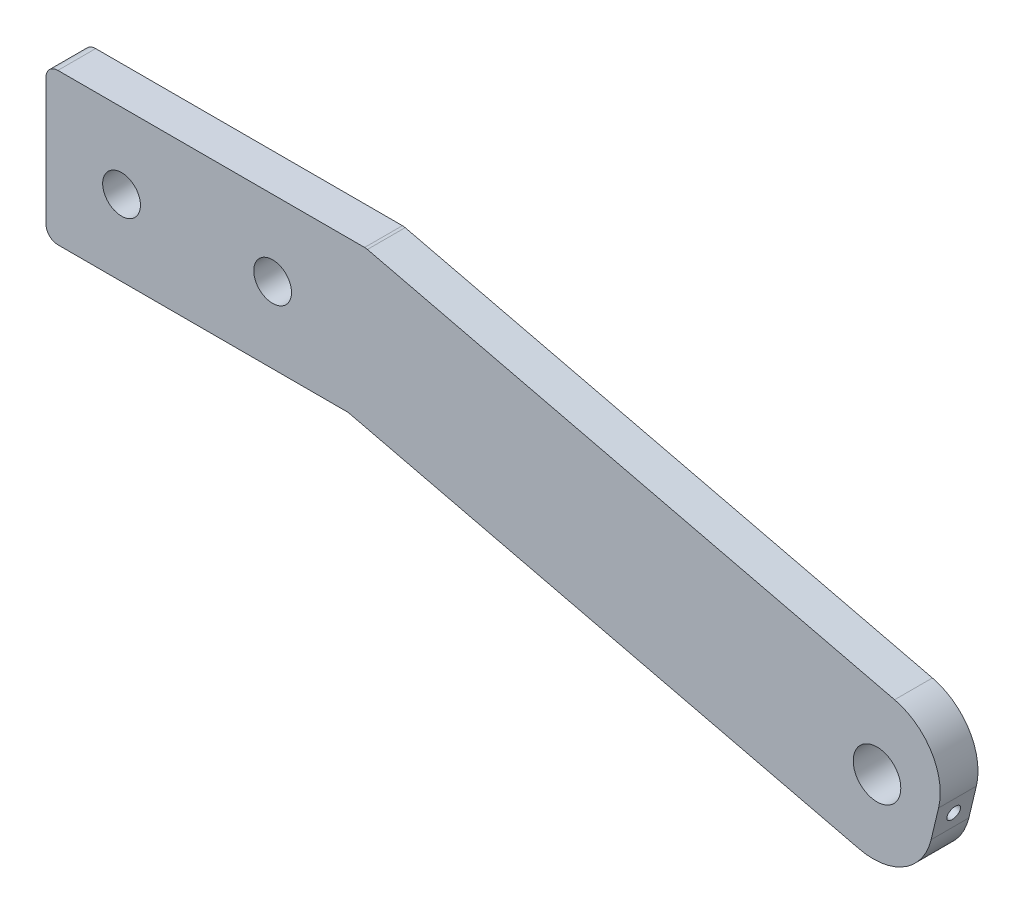
SolidWorks part; units mm, degrees
ref_plane "Front Plane" through (0, 0, 0) normal (0, 0, 1) x (1, 0, 0)
ref_plane "Top Plane" through (0, 0, 0) normal (0, 1, 0) x (1, 0, 0)
ref_plane "Right Plane" through (0, 0, 0) normal (1, 0, 0) x (0, 0, -1)
sketch "Sketch1" plane through (0, 0, 0) normal (0, 0, 1) x (1, 0, 0)
  line L0 (-25.4, 0) -> (-38.1, 0) construction
  line L2 (-38.1, -12.7) -> (-38.1, 12.7)
  line L5 (104.5604, -8.5999) -> (98.6396, -33.3001) construction
  line L6 (12.7, -12.7) -> (71.3084, -26.7487) construction
  line L19 (-25.4, 0) -> (0, 0) construction
  line L25 (15.7017, 12.7) -> (-38.1, 12.7)
  line L26 (12.7, -12.7) -> (-38.1, -12.7)
  line L27 (15.7017, 12.7) -> (74.6646, -1.4337) construction
  line L28 (15.7017, 12.7) -> (114.2849, -10.9309)
  line L29 (12.7, -12.7) -> (108.3641, -35.6312)
  line L30 (108.3641, -35.6312) -> (114.2849, -10.9309)
  circle A0 centre (-25.4, 0) radius 3.175
  circle A12 centre (0, 0) radius 3.175
  circle A13 centre (101.6, -20.95) radius 4
  point P8 (0, 0)
  point P16 (64.2348, -43.9487)
  point P17 (0, 0)
  dimension "D4" = 6.35
  dimension "D7" = 10
  dimension "D8" = 25.4
  dimension "D5" = 101.6
  dimension "D6" = 20.95
  dimension "D9" = 8
  dimension "D2" = 50.8
  dimension "D3" = 12.7
  dimension "D12" = 25.4
  dimension "D13" = 25.4
extrude "Boss-Extrude1" add sketch "Sketch1" along normal blind 6.35
sketch "Sketch3" plane through (110.5529, -26.5001, 0) normal (0.9725, -0.2331, 0) x (0, 0, -1)
  line L0 (-6.35, 3.3102) -> (0, 3.3102) construction
  line L1 (-6.35, -9.3898) -> (-6.35, 16.0102) construction
  line L2 (0, -9.3898) -> (0, 16.0102) construction
  circle A0 centre (-3.175, 3.3102) radius 1.1303
  dimension "D1" = 2.2606
extrude "Cut-Extrude2" cut sketch "Sketch3" against normal up to next
fillet "Fillet3" radius 2 4 edges at (-38.1, -12.7, 3.175) (-38.1, 12.7, 3.175) (12.7, -12.7, 3.175) (15.7017, 12.7, 3.175)
fillet "Fillet4" radius 10 2 edges at (108.3641, -35.6312, 3.175) (114.2849, -10.9309, 3.175)
